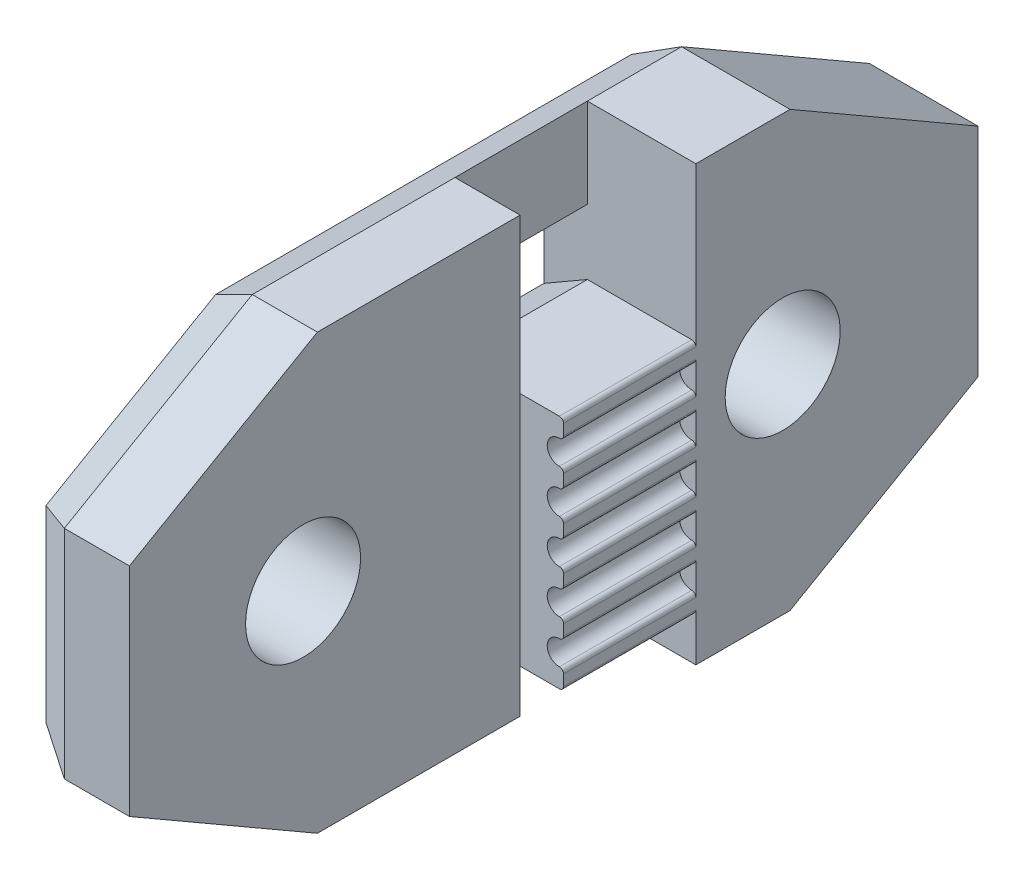
SolidWorks part; units mm, degrees
material "ABS"
ref_plane "Ebene vorne" through (0, 0, 0) normal (0, 0, 1) x (1, 0, 0)
ref_plane "Ebene oben" through (0, 0, 0) normal (0, 1, 0) x (1, 0, 0)
ref_plane "Ebene rechts" through (0, 0, 0) normal (1, 0, 0) x (0, 0, -1)
sketch "Skizze1" plane through (0, 0, 0) normal (0, 0, 1) x (1, 0, 0)
  line L0 (0, 0) -> (0, 9.44)
  line L1 (0, 9.44) -> (-7.24, 9.44) construction
  line L2 (-7.05, 10.19) -> (-7.05, 10.69)
  line L3 (-7.05, 8.69) -> (-7.05, 8.19)
  line L4 (-7.24, 10.88) -> (-9.24, 10.88)
  line L5 (-9.24, 10.88) -> (-9.24, 0)
  line L6 (-7.05, 6.69) -> (-7.05, 6.19)
  line L7 (-7.05, 4.69) -> (-7.05, 4.19)
  line L8 (-7.05, 2.69) -> (-7.05, 2.19)
  line L9 (-7.05, 0.69) -> (-7.05, 0.19)
  line L10 (-7.05, -1.31) -> (-7.05, -1.81) construction
  line L11 (-7.05, -3.31) -> (-7.05, -3.81) construction
  line L12 (-7.05, -5.31) -> (-7.05, -5.81) construction
  line L13 (-7.05, -7.31) -> (-7.05, -7.81) construction
  line L14 (-7.05, -9.31) -> (-7.05, -9.81) construction
  line L15 (-7.24, 0) -> (-9.24, 0)
  line L16 (0, 9.44) -> (0, 10.88)
  line L17 (0, 10.88) -> (-6, 10.88)
  line L18 (-6, 10.88) -> (-6, 0)
  line L19 (-6, 0) -> (0, 0)
  arc A0 (-7.24, 10) -> (-7.24, 8.88) centre (-7.24, 9.44) ccw
  arc A1 (-7.24, 8) -> (-7.24, 6.88) centre (-7.24, 7.44) ccw
  arc A2 (-7.05, 8.69) -> (-7.24, 8.88) centre (-7.24, 8.69) ccw
  arc A3 (-7.24, 8) -> (-7.05, 8.19) centre (-7.24, 8.19) ccw
  arc A4 (-7.05, 10.19) -> (-7.24, 10) centre (-7.24, 10.19) cw
  arc A5 (-7.24, 10.88) -> (-7.05, 10.69) centre (-7.24, 10.69) cw
  arc A6 (-7.24, 8) -> (-7.24, 6.88) centre (-7.24, 7.44) ccw
  arc A7 (-7.05, 6.69) -> (-7.24, 6.88) centre (-7.24, 6.69) ccw
  arc A8 (-7.24, 6) -> (-7.05, 6.19) centre (-7.24, 6.19) ccw
  arc A9 (-7.24, 6) -> (-7.24, 4.88) centre (-7.24, 5.44) ccw
  arc A10 (-7.05, 4.69) -> (-7.24, 4.88) centre (-7.24, 4.69) ccw
  arc A11 (-7.24, 4) -> (-7.05, 4.19) centre (-7.24, 4.19) ccw
  arc A12 (-7.24, 4) -> (-7.24, 2.88) centre (-7.24, 3.44) ccw
  arc A13 (-7.05, 2.69) -> (-7.24, 2.88) centre (-7.24, 2.69) ccw
  arc A14 (-7.24, 2) -> (-7.05, 2.19) centre (-7.24, 2.19) ccw
  arc A15 (-7.24, 2) -> (-7.24, 0.88) centre (-7.24, 1.44) ccw
  arc A16 (-7.05, 0.69) -> (-7.24, 0.88) centre (-7.24, 0.69) ccw
  arc A17 (-7.24, 0) -> (-7.05, 0.19) centre (-7.24, 0.19) ccw
  arc A18 (-7.24, 0) -> (-7.24, -1.12) centre (-7.24, -0.56) ccw construction
  arc A19 (-7.05, -1.31) -> (-7.24, -1.12) centre (-7.24, -1.31) ccw construction
  arc A20 (-7.24, -2) -> (-7.05, -1.81) centre (-7.24, -1.81) ccw construction
  arc A21 (-7.24, -2) -> (-7.24, -3.12) centre (-7.24, -2.56) ccw construction
  arc A22 (-7.05, -3.31) -> (-7.24, -3.12) centre (-7.24, -3.31) ccw construction
  arc A23 (-7.24, -4) -> (-7.05, -3.81) centre (-7.24, -3.81) ccw construction
  arc A24 (-7.24, -4) -> (-7.24, -5.12) centre (-7.24, -4.56) ccw construction
  arc A25 (-7.05, -5.31) -> (-7.24, -5.12) centre (-7.24, -5.31) ccw construction
  arc A26 (-7.24, -6) -> (-7.05, -5.81) centre (-7.24, -5.81) ccw construction
  arc A27 (-7.24, -6) -> (-7.24, -7.12) centre (-7.24, -6.56) ccw construction
  arc A28 (-7.05, -7.31) -> (-7.24, -7.12) centre (-7.24, -7.31) ccw construction
  arc A29 (-7.24, -8) -> (-7.05, -7.81) centre (-7.24, -7.81) ccw construction
  arc A30 (-7.24, -8) -> (-7.24, -9.12) centre (-7.24, -8.56) ccw construction
  arc A31 (-7.05, -9.31) -> (-7.24, -9.12) centre (-7.24, -9.31) ccw construction
  arc A32 (-7.24, -10) -> (-7.05, -9.81) centre (-7.24, -9.81) ccw construction
  point P6 (-7.8, 9.44)
  dimension "D1" = 0.56
  dimension "D3" = 0.75
  dimension "D2" = 2
  dimension "D5" = 2
  dimension "D6" = 1.8
  dimension "D7" = 6
  dimension "D8" = 10.88
  dimension "D4" = 10
extrude "Aufsatz-Linear austragen1" add sketch "Skizze1" along normal blind 6.1
sketch "Skizze2" plane through (0, 0, 6.1) normal (0, 0, 1) x (1, 0, 0)
  line L1 (-6, 10.88) -> (0, 10.88)
  line L2 (-6, 10.88) -> (-6, 0)
  line L3 (-6, 0) -> (0, 0)
  line L4 (0, 10.88) -> (0, 0)
extrude "Schnitt-Linear austragen1" cut sketch "Skizze2" against normal up to surface (6.1 mm away) up to face at (-3, 5.44, 0)
sketch "Skizze3" plane through (-9.24, 0, 0) normal (-1, 0, 0) x (0, 0, 1)
  line L0 (6.1, 0) -> (0, 0) construction
  line L1 (0, -2) -> (-13, -2)
  line L2 (0, -2) -> (0, 18)
  line L3 (0, 18) -> (-13, 18)
  line L4 (-13, -2) -> (-13, 18)
  line L5 (0, 10.88) -> (0, 0) construction
  line L6 (-4, 8) -> (0, 8) construction
  line L7 (6.1, 10.88) -> (6.1, 0) construction
  line L8 (0, 18) -> (6.1, 18)
  line L9 (0, 18) -> (0, 13.88)
  line L10 (0, 13.88) -> (6.1, 13.88)
  line L11 (6.1, 18) -> (6.1, 13.88)
  line L12 (6.1, 10.88) -> (0, 10.88) construction
  circle A0 centre (-4, 8) radius 2.65
  dimension "D4" = 5.3
  dimension "D1" = 20
  dimension "D2" = 2
  dimension "D3" = 4
  dimension "D5" = 13
  dimension "D6" = 3
extrude "Aufsatz-Linear austragen2" add sketch "Skizze3" against normal blind 2.19
sketch "Skizze4" plane through (-9.24, 0, 0) normal (-1, 0, 0) x (0, 0, 1)
  line L1 (6.1, 18) -> (24.1, 18)
  line L2 (6.1, 18) -> (6.1, -2)
  line L3 (6.1, -2) -> (24.1, -2)
  line L4 (24.1, 18) -> (24.1, -2)
  line L10 (6.1, 10.88) -> (0, 10.88)
  line L11 (0, 10.88) -> (0, 13.88)
  line L12 (0, 13.88) -> (6.1, 13.88)
  line L13 (6.1, 13.88) -> (6.1, 18)
  line L14 (6.1, 18) -> (-13, 18)
  line L15 (-13, 18) -> (-13, -2)
  line L16 (-13, -2) -> (0, -2)
  line L17 (0, -2) -> (0, 0)
  line L18 (0, 0) -> (6.1, 0)
  line L19 (6.1, 0) -> (6.1, 10.88)
  line L20 (6.1, 10.88) -> (0, 10.88)
  line L21 (0, 10.88) -> (0, 13.88)
  line L22 (0, 13.88) -> (6.1, 13.88)
  line L23 (6.1, 13.88) -> (6.1, 18)
  line L24 (6.1, 18) -> (-13, 18)
  line L25 (-13, 18) -> (-13, -2)
  line L26 (-13, -2) -> (0, -2)
  line L27 (0, -2) -> (0, 0)
  line L28 (0, 0) -> (6.1, 0)
  line L29 (6.1, 0) -> (6.1, 10.88)
  circle A0 centre (-4, 8) radius 2.65 construction
  circle A1 centre (-4, 8) radius 2.65
  circle A2 centre (16.1, 8) radius 2.65
  line M11 (6.1, 10.88) -> (0, 10.88)
  line M12 (0, 10.88) -> (0, 13.88)
  line M13 (0, 13.88) -> (6.1, 13.88)
  line M14 (6.1, 13.88) -> (6.1, 18)
  line M15 (6.1, 18) -> (-13, 18)
  line M16 (-13, 18) -> (-13, -2)
  line M17 (-13, -2) -> (0, -2)
  line M18 (0, -2) -> (0, 0)
  line M19 (0, 0) -> (6.1, 0)
  line M20 (6.1, 0) -> (6.1, 10.88)
  circle M21 centre (-4, 8) radius 2.65
  dimension "D2" = 10
  dimension "D3" = 8
  dimension "D1" = 0
extrude "Aufsatz-Linear austragen3" add sketch "Skizze4" along normal offset from surface (4.81 mm away) 7 contours L4 L1 L2 L3 A2 M14 M20 | M20 M11 M12 M13 M14 M15 M16 M17 M18 M19 M21 up to face at (-7.05, 6.344, 1.98)
sketch "Skizze5" plane through (-9.24, 0, 0) normal (1, 0, 0) x (0, 0, -1)
  line L7 (-6.1, 13.88) -> (-6.1, 18)
  line L8 (-6.1, 18) -> (-24.1, 18)
  line L9 (-24.1, 18) -> (-24.1, -2)
  line L10 (-24.1, -2) -> (-6.1, -2)
  line L11 (-6.1, -2) -> (-6.1, 0)
  line L12 (-6.1, 0) -> (-6.1, 10.88)
  line L13 (-6.1, 10.88) -> (-6.1, 13.88)
  line L14 (-6.1, 13.88) -> (-6.1, 18)
  line L15 (-6.1, 18) -> (-24.1, 18)
  line L16 (-24.1, 18) -> (-24.1, -2)
  line L17 (-24.1, -2) -> (-6.1, -2)
  line L18 (-6.1, -2) -> (-6.1, 0)
  line L19 (-6.1, 0) -> (-6.1, 10.88)
  line L20 (-6.1, 10.88) -> (-6.1, 13.88)
  circle A0 centre (-16.1, 8) radius 2.65 construction
  circle A1 centre (-16.1, 8) radius 2.65
  dimension "D1" = 0
extrude "Aufsatz-Linear austragen4" add sketch "Skizze5" along normal offset from surface (0.19 mm away) 2 up to face at (-7.05, 6.344, 1.98)
chamfer "Fase1" distance 5 angle 60 4 edges at (-10.55, 18, -13) (-11.55, 18, 24.1) (-11.55, -2, 24.1) (-10.55, -2, -13)
chamfer "Fase2" distance 2 angle 30 11 edges at (-14.05, 10.88, 3.05) (-14.05, 13.88, 3.05) (-14.05, -2, -2.1699) (-14.05, -2, 10.7699) (-14.05, 0.5, 19.7699) (-14.05, 8, 24.1) (-14.05, 15.5, 19.7699) (-14.05, 18, 5.55) (-14.05, 15.5, -8.6699) (-14.05, 8, -13) (-14.05, 0.5, -8.6699)
sketch "Skizze11" plane through (0, -2, 0) normal (0, -1, 0) x (1, 0, 0)
  line L0 (-14.05, 7.6) -> (-14.05, 6.1)
  line L1 (-14.05, 6.1) -> (-14.05, 15.1303) construction
  line L2 (-14.05, 0) -> (-14.05, -1.5)
  line L3 (-12.55, 1.5) -> (-12.55, 4.6)
  line L4 (-11.05, 1.5) -> (-11.05, 4.6)
  arc A0 (-14.05, 6.1) -> (-12.55, 4.6) centre (-14.05, 4.6) cw
  arc A1 (-14.05, 0) -> (-12.55, 1.5) centre (-14.05, 1.5) ccw
  arc A2 (-14.05, -1.5) -> (-11.05, 1.5) centre (-14.05, 1.5) ccw
  arc A3 (-14.05, 7.6) -> (-11.05, 4.6) centre (-14.05, 4.6) cw
  dimension "D1" = 1.5
  dimension "D2" = 1.5
extrude "Schnitt-Linear austragen3" cut sketch "Skizze11" against normal blind 2.5 from offset 4
sketch "Skizze12" plane through (0, 18, 0) normal (0, 1, 0) x (1, 0, 0)
  line L0 (-7.24, 0) -> (-12.05, 0) construction
  line L1 (-7.05, -6.1) -> (-12.05, -6.1)
  line L2 (-7.05, -6.1) -> (-7.05, 0)
  line L3 (-7.05, 0) -> (-12.05, 0)
  line L4 (-12.05, -6.1) -> (-12.05, 0)
  line L5 (-14.05, -15.1303) -> (-14.05, 4.0303) construction
  dimension "D1" = 2
  dimension "D2" = 5
extrude "Schnitt-Linear austragen4" cut sketch "Skizze12" against normal up to surface (4.12 mm away) up to face at (-9.45, 13.88, 3.66)
